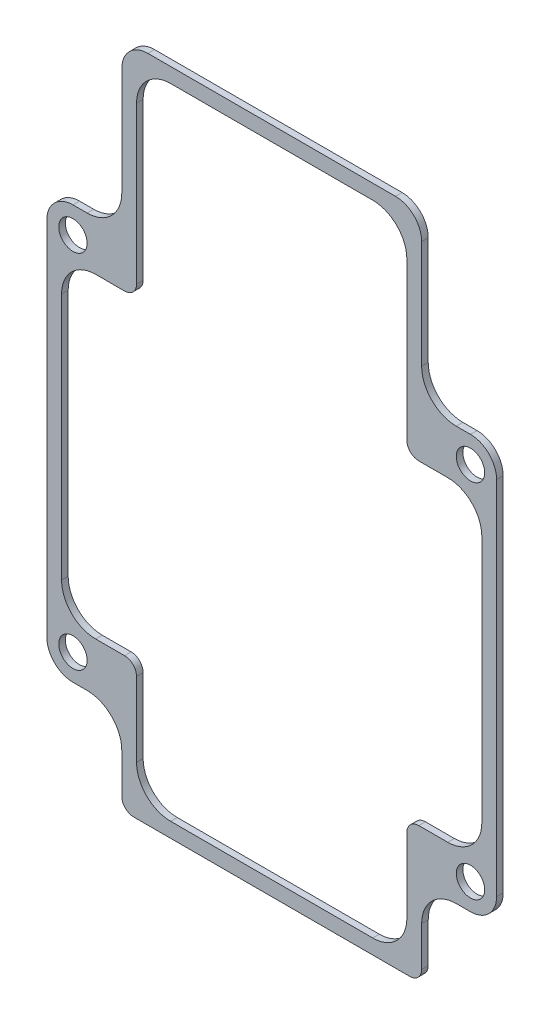
SolidWorks part; units mm, degrees
ref_plane "Front Plane" through (0, 0, 0) normal (0, 0, 1) x (1, 0, 0)
ref_plane "Top Plane" through (0, 0, 0) normal (0, 1, 0) x (1, 0, 0)
ref_plane "Right Plane" through (0, 0, 0) normal (1, 0, 0) x (0, 0, -1)
sketch "Sketch1" plane through (0, 0, 0) normal (0, 0, 1) x (1, 0, 0)
  line L88 (15.113, -27.305) -> (15.113, -18.9865)
  line L89 (16.4465, -17.653) -> (19.685, -17.653)
  line L90 (23.495, -13.843) -> (23.495, 13.843)
  line L91 (19.685, 17.653) -> (16.4465, 17.653)
  line L92 (15.113, 18.9865) -> (15.113, 36.5125)
  line L93 (11.303, 40.3225) -> (-11.303, 40.3225)
  line L94 (-15.113, 36.5125) -> (-15.113, 18.9865)
  line L95 (-16.4465, 17.653) -> (-19.685, 17.653)
  line L96 (-23.495, 13.843) -> (-23.495, -13.843)
  line L97 (-19.685, -17.653) -> (-16.4465, -17.653)
  line L98 (-15.113, -18.9865) -> (-15.113, -27.305)
  line L99 (-11.303, -31.115) -> (11.303, -31.115)
  line L130 (-16.764, -26.9875) -> (-16.764, -31.4325)
  line L136 (13.843, 41.9735) -> (-13.843, 41.9735)
  line L137 (-16.764, 39.0525) -> (-16.764, 26.9875)
  line L138 (-20.6375, 23.114) -> (-22.225, 23.114)
  line L139 (-25.146, 20.193) -> (-25.146, -20.193)
  line L140 (-22.225, -23.114) -> (-20.6375, -23.114)
  line L144 (20.6375, -23.114) -> (22.225, -23.114)
  line L145 (25.146, -20.193) -> (25.146, 20.193)
  line L146 (22.225, 23.114) -> (20.6375, 23.114)
  line L147 (16.764, 26.9875) -> (16.764, 39.0525)
  line L564 (-15.4305, -32.766) -> (15.4305, -32.766)
  line L566 (16.764, -31.4325) -> (16.764, -26.9875)
  circle A64 centre (-22.225, 20.193) radius 1.5875
  circle A66 centre (22.225, 20.193) radius 1.5875
  circle A67 centre (22.225, -20.193) radius 1.5875
  arc A100 (16.4465, -17.653) -> (15.113, -18.9865) centre (16.4465, -18.9865) ccw
  arc A101 (19.685, -17.653) -> (23.495, -13.843) centre (19.685, -13.843) ccw
  arc A102 (23.495, 13.843) -> (19.685, 17.653) centre (19.685, 13.843) ccw
  arc A103 (15.113, 18.9865) -> (16.4465, 17.653) centre (16.4465, 18.9865) ccw
  arc A104 (15.113, 36.5125) -> (11.303, 40.3225) centre (11.303, 36.5125) ccw
  arc A105 (-11.303, 40.3225) -> (-15.113, 36.5125) centre (-11.303, 36.5125) ccw
  arc A106 (-16.4465, 17.653) -> (-15.113, 18.9865) centre (-16.4465, 18.9865) ccw
  arc A107 (-19.685, 17.653) -> (-23.495, 13.843) centre (-19.685, 13.843) ccw
  arc A108 (-23.495, -13.843) -> (-19.685, -17.653) centre (-19.685, -13.843) ccw
  arc A109 (-15.113, -18.9865) -> (-16.4465, -17.653) centre (-16.4465, -18.9865) ccw
  arc A110 (-15.113, -27.305) -> (-11.303, -31.115) centre (-11.303, -27.305) ccw
  arc A111 (11.303, -31.115) -> (15.113, -27.305) centre (11.303, -27.305) ccw
  circle A128 centre (-22.225, -20.193) radius 1.5875
  arc A145 (-16.764, -26.9875) -> (-20.6375, -23.114) centre (-20.6375, -26.9875) ccw
  arc A147 (-16.764, -31.4325) -> (-15.4305, -32.766) centre (-15.4305, -31.4325) ccw
  arc A152 (-13.843, 41.9735) -> (-16.764, 39.0525) centre (-13.843, 39.0525) ccw
  arc A153 (-20.6375, 23.114) -> (-16.764, 26.9875) centre (-20.6375, 26.9875) ccw
  arc A154 (-22.225, 23.114) -> (-25.146, 20.193) centre (-22.225, 20.193) ccw
  arc A155 (-25.146, -20.193) -> (-22.225, -23.114) centre (-22.225, -20.193) ccw
  arc A160 (22.225, -23.114) -> (25.146, -20.193) centre (22.225, -20.193) ccw
  arc A161 (25.146, 20.193) -> (22.225, 23.114) centre (22.225, 20.193) ccw
  arc A162 (16.764, 26.9875) -> (20.6375, 23.114) centre (20.6375, 26.9875) ccw
  arc A163 (16.764, 39.0525) -> (13.843, 41.9735) centre (13.843, 39.0525) ccw
  arc A562 (15.4305, -32.766) -> (16.764, -31.4325) centre (15.4305, -31.4325) ccw
  arc A564 (20.6375, -23.114) -> (16.764, -26.9875) centre (20.6375, -26.9875) ccw
  dimension "D3" = 3.175
extrude "Boss-Extrude1" add sketch "Sketch1" along normal blind 0.7366
